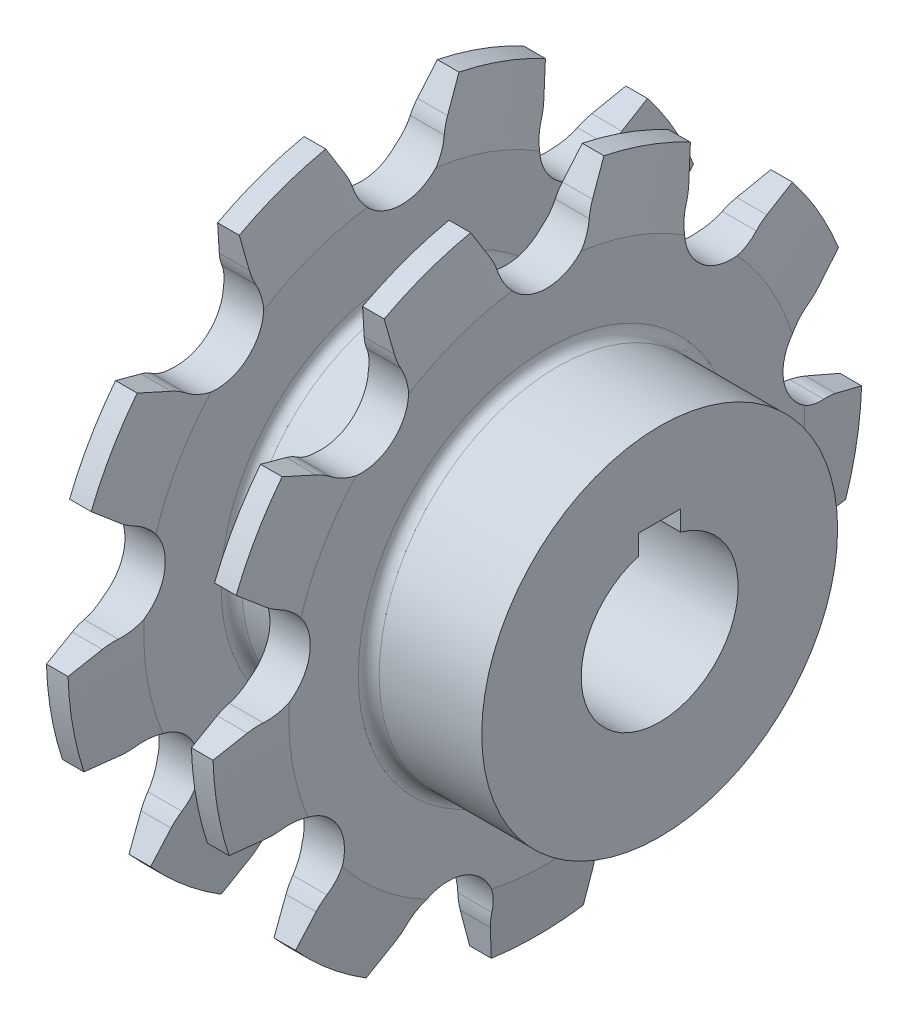
SolidWorks part; units mm, degrees
ref_plane "前基準面" through (0, 0, 0) normal (0, 0, 1) x (1, 0, 0)
ref_plane "上基準面" through (0, 0, 0) normal (0, 1, 0) x (1, 0, 0)
ref_plane "右基準面" through (0, 0, 0) normal (1, 0, 0) x (0, 0, -1)
sketch "草圖1" plane through (0, 0, 0) normal (0, 0, 1) x (1, 0, 0)
  line L0 (0, 0) -> (82.9174, 0) construction
  line L1 (0, 0) -> (0, 49.3)
  line L2 (1.7849, 62) -> (5.9151, 62)
  line L3 (7.7, 49.3) -> (7.7, 34.5)
  line L4 (9.7, 32.5) -> (25.7, 32.5)
  line L5 (27.7, 34.5) -> (27.7, 49.3)
  line L6 (0, 0) -> (57, 0)
  line L7 (35.4, 49.3) -> (35.4, 36)
  line L8 (37.4, 34) -> (57, 34)
  line L9 (57, 34) -> (57, 0)
  line L10 (5.9151, 62) -> (29.4849, 62) construction
  line L11 (1.7849, 62) -> (0, 49.3)
  line L12 (3.85, 62) -> (3.85, 0) construction
  line L13 (5.9151, 62) -> (7.7, 49.3)
  line L14 (0, 49.3) -> (7.7, 49.3) construction
  line L15 (7.7, 49.3) -> (35.4, 49.3) construction
  line L16 (33.6151, 62) -> (35.4, 49.3)
  line L17 (33.6151, 62) -> (29.4849, 62)
  line L18 (29.4849, 62) -> (27.7, 49.3)
  arc A0 (37.4, 34) -> (35.4, 36) centre (37.4, 36) cw
  arc A1 (27.7, 34.5) -> (25.7, 32.5) centre (25.7, 34.5) cw
  arc A2 (9.7, 32.5) -> (7.7, 34.5) centre (9.7, 34.5) cw
  dimension "D11" = 2
  dimension "D1" = 57
  dimension "D2" = 7.7
  dimension "D5" = 32.5
  dimension "D6" = 62
  dimension "D7" = 34
  dimension "D8" = 49.3
  dimension "D9" = 8
  dimension "D10" = 8
revolve "旋轉3" add sketch "草圖1" angle 360 about L0
sketch "草圖2" plane through (57, 0, 0) normal (1, 0, 0) x (0, 0, -1)
  line L0 (0, -34) -> (0, 34) construction
  line L2 (-4, 18.3) -> (4, 18.3)
  line L3 (-4, 18.3) -> (-4, 14.4568)
  line L5 (4, 18.3) -> (4, 14.4568)
  arc A0 (-4, 14.4568) -> (4, 14.4568) centre (0, 0) ccw
  circle A1 centre (0, 0) radius 34 construction
  circle A2 centre (0, 0) radius 34 construction
  dimension "D1" = 30
  dimension "D2" = 8
  dimension "D3" = 18.3
extrude "除料-伸長1" cut sketch "草圖2" against normal through all
sketch "草圖3" plane through (0, 0, 0) normal (-1, 0, 0) x (0, 0, 1)
  line L0 (0, 62) -> (0, -62) construction
  line L1 (0, 0) -> (-8.8131, 53.1317) construction
  line L2 (0, 0) -> (8.8131, 53.1317) construction
  line L3 (-12.731, 60.6788) -> (-9.7395, 55.3735)
  line L5 (12.731, 60.6788) -> (9.7395, 55.3735)
  arc A0 (0, 55) -> (9.1013, 54.2417) centre (0, 0) ccw construction
  circle A1 centre (0, 0) radius 62 construction
  arc A2 (-8.7395, 52.8503) -> (8.7395, 52.8503) centre (0, 55) ccw
  arc A3 (12.731, 60.6788) -> (-12.731, 60.6788) centre (0, 0) ccw
  arc A4 (9.7395, 55.3735) -> (8.7395, 52.8503) centre (18.4501, 50.4618) ccw
  arc A6 (-9.7395, 55.3735) -> (-8.7395, 52.8503) centre (-18.4501, 50.4618) cw
  point P31 (0, 0)
  point P57 (0, 0)
  dimension "D1" = 110
  dimension "D2" = 18
  dimension "D5" = 20
extrude "除料-伸長2" cut sketch "草圖3" against normal through all
pattern_circular "環狀複製排列10" count 9 over 360 about axis through (0, 0, 0) along (1, 0, 0) of "除料-伸長2"
